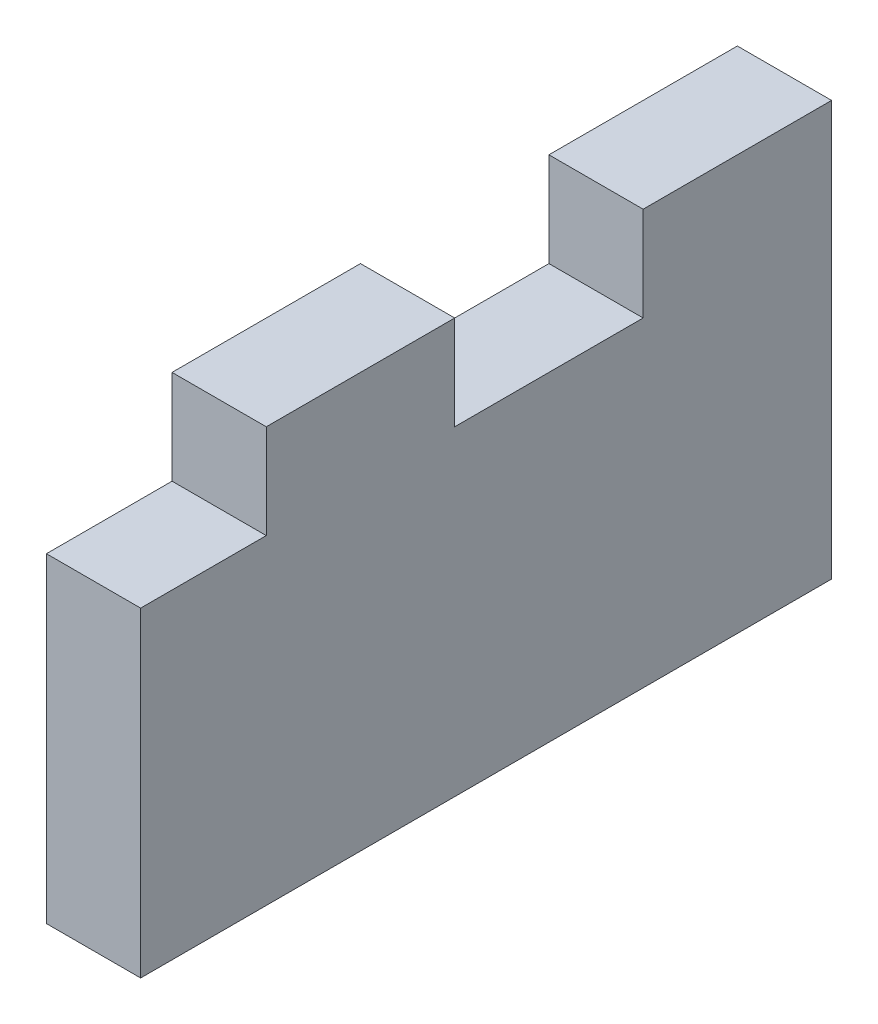
SolidWorks part; units mm, degrees
ref_plane "Front Plane" through (0, 0, 0) normal (0, 0, 1) x (1, 0, 0)
ref_plane "Top Plane" through (0, 0, 0) normal (0, 1, 0) x (1, 0, 0)
ref_plane "Right Plane" through (0, 0, 0) normal (1, 0, 0) x (0, 0, -1)
sketch "Sketch2" plane through (0, 0, 0) normal (1, 0, 0) x (0, 0, -1)
  line L1 (0, 0) -> (69.85, 0)
  line L2 (0, 0) -> (0, 32.385)
  line L3 (12.7, 41.91) -> (69.85, 41.91)
  line L4 (69.85, 0) -> (69.85, 41.91)
  line L7 (0, 32.385) -> (12.7, 32.385)
  line L8 (12.7, 41.91) -> (12.7, 32.385)
  line L9 (31.75, 32.385) -> (50.8, 32.385)
  line L10 (31.75, 32.385) -> (31.75, 41.91)
  line L11 (31.75, 41.91) -> (50.8, 41.91)
  line L12 (50.8, 32.385) -> (50.8, 41.91)
  dimension "D1" = 41.91
  dimension "D2" = 9.525
  dimension "D3" = 12.7
  dimension "D4" = 19.05
  dimension "D5" = 19.05
  dimension "D6" = 19.05
extrude "Boss-Extrude1" add sketch "Sketch2" along normal blind 9.525 contours L12 L9 L10 L3 L8 L7 L2 L1 L4
